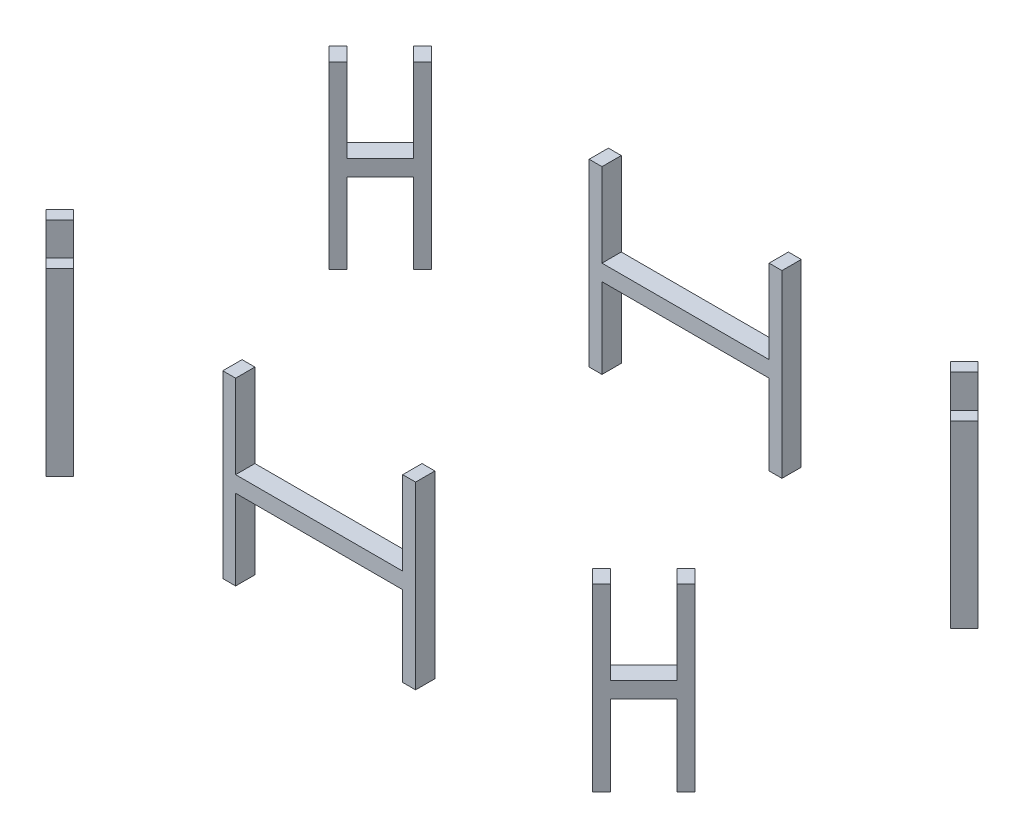
SolidWorks part; units mm, degrees
ref_plane "前视基准面" through (0, 0, 0) normal (0, 0, 1) x (1, 0, 0)
ref_plane "上视基准面" through (0, 0, 0) normal (0, 1, 0) x (1, 0, 0)
ref_plane "右视基准面" through (0, 0, 0) normal (1, 0, 0) x (0, 0, -1)
sketch "草图1" plane through (0, 0, 0) normal (0, 1, 0) x (1, 0, 0)
  line L8 (-505, 220) -> (-425, 300)
  line L12 (-425, 300) -> (-403.7868, 278.7868)
  line L13 (-403.7868, 278.7868) -> (-483.7868, 198.7868)
  line L14 (-505, 220) -> (-483.7868, 198.7868)
  line L15 (-150, 270) -> (150, 270)
  line L16 (0, 300) -> (-150, 300)
  line L17 (-150, 300) -> (-150, 270)
  line L18 (0, 300) -> (150, 300)
  line L19 (150, 300) -> (150, 270)
  line L20 (0, 0) -> (0, 106.1612) construction
  line L21 (0, 0) -> (94.5244, 0) construction
  line L22 (505, 220) -> (483.7868, 198.7868)
  line L23 (403.7868, 278.7868) -> (483.7868, 198.7868)
  line L24 (425, 300) -> (403.7868, 278.7868)
  line L25 (505, 220) -> (425, 300)
  line L26 (505, -220) -> (425, -300)
  line L27 (425, -300) -> (403.7868, -278.7868)
  line L28 (403.7868, -278.7868) -> (483.7868, -198.7868)
  line L29 (505, -220) -> (483.7868, -198.7868)
  line L30 (-150, -300) -> (-150, -270)
  line L31 (0, -300) -> (-150, -300)
  line L32 (0, -300) -> (150, -300)
  line L33 (150, -300) -> (150, -270)
  line L34 (-150, -270) -> (150, -270)
  line L35 (-505, -220) -> (-483.7868, -198.7868)
  line L36 (-403.7868, -278.7868) -> (-483.7868, -198.7868)
  line L37 (-425, -300) -> (-403.7868, -278.7868)
  line L38 (-505, -220) -> (-425, -300)
  point P3 (-505, 300)
  point P5 (505, 300)
  point P6 (505, -300)
  point P7 (-505, -300)
extrude "凸台-拉伸1" add sketch "草图1" along normal blind 280
sketch "草图2" plane through (0, 0, 300) normal (0, 0, 1) x (1, 0, 0)
  line L1 (-150, 280) -> (150, 280) construction
  line L3 (130, 280) -> (130, 150)
  line L4 (-130, 280) -> (-130, 150)
  line L5 (-130, 280) -> (130, 280)
  line L6 (130, 150) -> (-130, 150)
  line L8 (130, 0) -> (130, 125)
  line L9 (130, 125) -> (-130, 125)
  line L10 (-130, 0) -> (-130, 125)
  line L11 (-130, 0) -> (130, 0)
extrude "切除-拉伸1" cut sketch "草图2" against normal through all both and the other way through all
sketch "草图3" plane through (362.5, 0, 362.5) normal (0.7071, 0, 0.7071) x (0.7071, 0, -0.7071)
  line L1 (88.3883, 280) -> (201.5254, 280) construction
  line L2 (108.3883, 280) -> (108.3883, 150)
  line L4 (181.5254, 280) -> (181.5254, 150)
  line L5 (181.5254, 150) -> (108.3883, 150)
  line L6 (108.3883, 280) -> (181.5254, 280)
  line L8 (181.5254, 0) -> (181.5254, 125)
  line L9 (181.5254, 125) -> (108.3883, 125)
  line L10 (108.3883, 0) -> (108.3883, 125)
  line L11 (108.3883, 0) -> (181.5254, 0)
extrude "切除-拉伸2" cut sketch "草图3" against normal blind 30
sketch "草图4" plane through (362.5, 0, -362.5) normal (0.7071, 0, -0.7071) x (-0.7071, 0, -0.7071)
  line L0 (-181.5254, 280) -> (-108.3883, 280)
  line L1 (-201.5254, 280) -> (-88.3883, 280) construction
  line L2 (-181.5254, 280) -> (-181.5254, 150)
  line L3 (-201.5254, 140) -> (-88.3883, 140) construction
  line L4 (-108.3883, 280) -> (-108.3883, 150)
  line L5 (-108.3883, 150) -> (-181.5254, 150)
  line L6 (-201.5254, 280) -> (-201.5254, 0) construction
  line L7 (-88.3883, 280) -> (-88.3883, 0) construction
  line L8 (-181.5254, 0) -> (-181.5254, 130)
  line L9 (-108.3883, 130) -> (-181.5254, 130)
  line L10 (-108.3883, 0) -> (-108.3883, 130)
  line L11 (-181.5254, 0) -> (-108.3883, 0)
extrude "切除-拉伸3" cut sketch "草图4" against normal blind 30
sketch "草图5" plane through (-362.5, 0, -362.5) normal (-0.7071, 0, -0.7071) x (-0.7071, 0, 0.7071)
  line L1 (88.3883, 280) -> (201.5254, 280) construction
  line L2 (108.3883, 280) -> (108.3883, 150)
  line L4 (181.5254, 280) -> (181.5254, 150)
  line L5 (181.5254, 150) -> (108.3883, 150)
  line L6 (108.3883, 280) -> (181.5254, 280)
  line L8 (181.5254, 0) -> (181.5254, 125)
  line L9 (181.5254, 125) -> (108.3883, 125)
  line L10 (108.3883, 0) -> (108.3883, 125)
  line L11 (108.3883, 0) -> (181.5254, 0)
extrude "切除-拉伸4" cut sketch "草图5" against normal blind 30
sketch "草图6" plane through (-362.5, 0, 362.5) normal (-0.7071, 0, 0.7071) x (0.7071, 0, 0.7071)
  line L0 (-201.5254, 140) -> (-88.3883, 140) construction
  line L1 (-201.5254, 280) -> (-88.3883, 280) construction
  line L2 (-181.5254, 280) -> (-181.5254, 150)
  line L3 (-201.5254, 280) -> (-201.5254, 0) construction
  line L4 (-108.3883, 280) -> (-108.3883, 150)
  line L5 (-108.3883, 150) -> (-181.5254, 150)
  line L6 (-181.5254, 280) -> (-108.3883, 280)
  line L7 (-88.3883, 280) -> (-88.3883, 0) construction
  line L8 (-108.3883, 0) -> (-108.3883, 130)
  line L9 (-108.3883, 130) -> (-181.5254, 130)
  line L10 (-181.5254, 0) -> (-181.5254, 130)
  line L11 (-181.5254, 0) -> (-108.3883, 0)
extrude "切除-拉伸5" cut sketch "草图6" against normal blind 30
